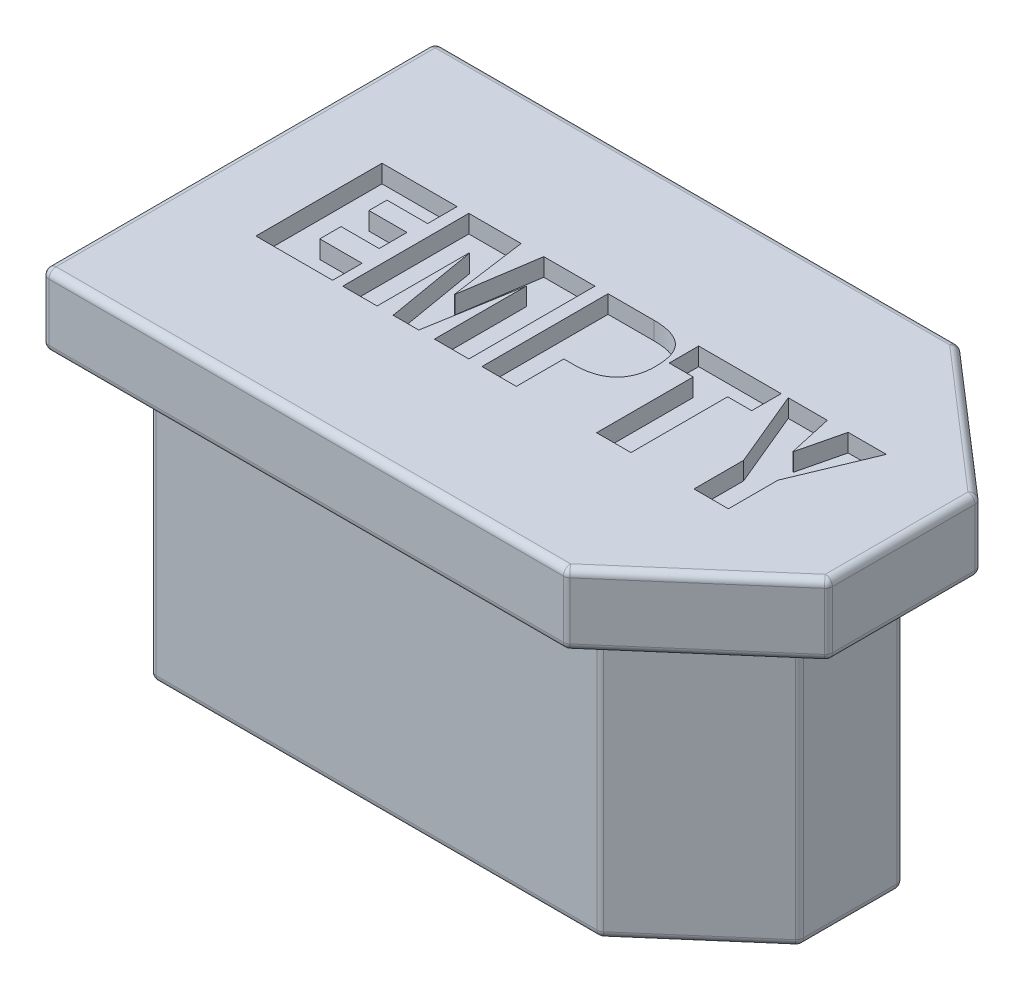
SolidWorks part; units mm, degrees
ref_plane "Front Plane" through (0, 0, 0) normal (0, 0, 1) x (1, 0, 0)
ref_plane "Top Plane" through (0, 0, 0) normal (0, 1, 0) x (1, 0, 0)
ref_plane "Right Plane" through (0, 0, 0) normal (1, 0, 0) x (0, 0, -1)
sketch "Sketch1" plane through (0, 0, 0) normal (0, 1, 0) x (1, 0, 0)
  line L0 (-7.8002, 4) -> (4.7998, 4)
  line L1 (4.7998, 4) -> (7.8002, 1.4)
  line L2 (7.8002, 1.4) -> (7.8002, -1.4)
  line L3 (7.8002, -1.4) -> (4.7998, -4)
  line L4 (4.7998, -4) -> (-7.8002, -4)
  line L5 (-7.8002, -4) -> (-7.8002, 4)
  line L6 (-7.8002, 0) -> (7.8002, 0) construction
  dimension "D1" = 8
  dimension "D2" = 12.6
  dimension "D3" = 139.09
  dimension "D4" = 2.8
extrude "Boss-Extrude1" add sketch "Sketch1" along normal mid plane 8
shell "Shell1" thickness 0.7
sketch "Sketch2" plane through (0, 4, 0) normal (0, 1, 0) x (1, 0, 0)
  line L0 (-7.8002, 4) -> (-7.8002, -4) construction
  line L1 (4.7998, 4) -> (-7.8002, 4) construction
  line L2 (7.8002, 1.4) -> (4.7998, 4) construction
  line L3 (7.8002, -1.4) -> (7.8002, 1.4) construction
  line L4 (4.7998, -4) -> (7.8002, -1.4) construction
  line L5 (-7.8002, -4) -> (4.7998, -4) construction
  line L6 (-7.8002, 4) -> (-7.8002, -4) construction
  line L7 (4.7998, 4) -> (-7.8002, 4) construction
  line L8 (7.8002, 1.4) -> (4.7998, 4) construction
  line L9 (7.8002, -1.4) -> (7.8002, 1.4) construction
  line L10 (4.7998, -4) -> (7.8002, -1.4) construction
  line L11 (-7.8002, -4) -> (4.7998, -4) construction
  line L12 (-9.3002, 5.5) -> (-9.3002, -5.5)
  line L13 (-9.3002, -5.5) -> (5.3593, -5.5)
  line L14 (5.3593, -5.5) -> (9.3002, -2.085)
  line L15 (9.3002, -2.085) -> (9.3002, 2.085)
  line L16 (9.3002, 2.085) -> (5.3593, 5.5)
  line L17 (5.3593, 5.5) -> (-9.3002, 5.5)
  dimension "D1" = 1.5
extrude "Boss-Extrude2" add sketch "Sketch2" along normal blind 2
sketch "Sketch4" plane through (0, -4, 0) normal (0, -1, 0) x (1, 0, 0)
  line L0 (-1.1002, -3.3) -> (-1.1002, -2.1)
  line L3 (4.5387, -3.3) -> (-7.1002, -3.3) construction
  line L5 (-1.1002, -2.1) -> (0.8998, -2.1)
  line L6 (0.8998, -2.1) -> (0.8998, -3.3)
  line L7 (-1.1002, -3.3) -> (0.8998, -3.3)
  dimension "D1" = 1.2
  dimension "D2" = 2
  dimension "D3" = 6
extrude "Boss-Extrude4" add sketch "Sketch4" against normal up to next
sketch "Sketch5" plane through (0, 4, 0) normal (0, -1, 0) x (1, 0, 0)
  line L0 (-0.6502, -2.1) -> (-0.6502, 1.9)
  line L1 (0.8998, -2.1) -> (-1.1002, -2.1) construction
  line L2 (-0.6502, 1.9) -> (0.4498, 1.9)
  line L3 (0.4498, 1.9) -> (0.4498, -2.1)
  line L4 (0.8998, -2.1) -> (-1.1002, -2.1) construction
  line L5 (0.4498, -2.1) -> (-0.6502, -2.1)
  line L6 (-0.1002, -2.1) -> (-0.1002, 1.9) construction
  dimension "D1" = 4
  dimension "D2" = 1.1
extrude "Cut-Extrude1" cut sketch "Sketch5" against normal blind 1
fillet "Fillet1" radius 0.2 78 edges at (4.5387, 0, -3.3) (7.1002, 0, -1.0803) (7.1002, 0, 1.0803) (4.5387, 0, 3.3) (-7.1002, 0, -3.3) (-1.1002, 0, -3.3) (-1.1002, 0, -2.1) (0.8998, 0, -2.1) (0.8998, 0, -3.3) (-7.1002, 0, 3.3) (0.8998, 4, -2.7) (0.8998, -4, -2.7) (2.7192, -4, -3.3) (-1.1002, 4, -2.7) (-1.1002, -4, -2.7) (-0.1002, 4, 1.9) (5.8195, -4, -2.1902) (-4.1002, -4, -3.3) (-0.1002, -4, -2.1) (-0.1002, 5, 1.9) (0.4498, 4.5, 1.9) (-0.6502, 4.5, 1.9) (0.4498, 5, -0.1) (-0.6502, 5, -0.1) (5.8195, 4, -2.1902) (2.7192, 4, -3.3) (-0.1002, 5, -2.1) (-4.1002, 4, -3.3) (7.1002, -4, 0) (7.1002, 4, 0) (-1.2808, -4, 3.3) (-1.2808, 4, 3.3) (5.8195, -4, 2.1902) (5.8195, 4, 2.1902) (-7.1002, -4, 0) (-7.1002, 4, 0) (-1.9705, 4, -5.5) (-9.3002, 4, 0) (-1.9705, 4, 5.5) (7.3297, 4, 3.7925) (9.3002, 4, 0) (7.3297, 4, -3.7925) (-1.9705, 6, -5.5) (-9.3002, 6, 0) (-1.9705, 6, 5.5) (7.3297, 6, 3.7925) (9.3002, 6, 0) (7.3297, 6, -3.7925) (5.3593, 5, -5.5) (9.3002, 5, -2.085) (9.3002, 5, 2.085) (5.3593, 5, 5.5) (-9.3002, 5, 5.5) (-9.3002, 5, -5.5) (-7.8002, -4, 0) (6.3, -4, 2.7) (7.8002, -4, 0) (6.3, -4, -2.7) (-1.5002, -4, -4) (-7.8002, 4, 0) (-1.5002, 4, 4) (6.3, 4, 2.7) (7.8002, 4, 0) (6.3, 4, -2.7) (-1.5002, 4, -4) (-7.8002, 0, -4) (4.7998, 0, -4) (7.8002, 0, -1.4) (7.8002, 0, 1.4) (4.7998, 0, 4) (-7.8002, 0, 4) (-1.5002, -4, 4)
sketch "Sketch6" plane through (0, 6, 0) normal (0, 1, 0) x (1, 0, 0)
  line L0 (-7.0504, 1.7632) -> (-4.9509, 1.7632)
  line L1 (-4.9509, 1.7632) -> (-4.9509, 0.9388)
  line L2 (-4.9509, 0.9388) -> (-6.0886, 0.9388)
  line L3 (-6.0886, 0.9388) -> (-6.0886, 0.4351)
  line L4 (-6.0886, 0.4351) -> (-5.0253, 0.4351)
  line L5 (-5.0253, 0.4351) -> (-5.0253, -0.3435)
  line L6 (-5.0253, -0.3435) -> (-6.0886, -0.3435)
  line L7 (-6.0886, -0.3435) -> (-6.0886, -0.9388)
  line L8 (-6.0886, -0.9388) -> (-4.9065, -0.9388)
  line L9 (-4.9065, -0.9388) -> (-4.9065, -1.7632)
  line L10 (-4.9065, -1.7632) -> (-7.0504, -1.7632)
  line L11 (-7.0504, -1.7632) -> (-7.0504, 1.7632)
  line L12 (-4.6231, 1.7632) -> (-3.1619, 1.7632)
  line L13 (-3.1619, 1.7632) -> (-2.8649, -0.3893)
  line L14 (-2.8649, -0.3893) -> (-2.8549, -0.3893)
  line L15 (-2.8549, -0.3893) -> (-2.5272, 1.7632)
  line L16 (-2.5272, 1.7632) -> (-1.0968, 1.7632)
  line L17 (-1.0968, 1.7632) -> (-1.0968, -1.7632)
  line L18 (-1.0968, -1.7632) -> (-2.0585, -1.7632)
  line L19 (-2.0585, -1.7632) -> (-2.0585, 0.8086)
  line L20 (-2.0585, 0.8086) -> (-2.4964, -1.7632)
  line L21 (-2.4964, -1.7632) -> (-3.2134, -1.7632)
  line L22 (-3.2134, -1.7632) -> (-3.6514, 0.8086)
  line L23 (-3.6514, 0.8086) -> (-3.6614, 0.8086)
  line L24 (-3.6614, 0.8086) -> (-3.6614, -1.7632)
  line L25 (-3.6614, -1.7632) -> (-4.6231, -1.7632)
  line L26 (-4.6231, -1.7632) -> (-4.6231, 1.7632)
  line L27 (-0.7304, 1.7632) -> (0.5527, 1.7632)
  line L28 (0.5333, -0.4351) -> (0.2314, -0.4351)
  line L29 (0.2314, -0.4351) -> (0.2314, -1.7632)
  line L30 (0.2314, -1.7632) -> (-0.7304, -1.7632)
  line L31 (-0.7304, 1.7632) -> (-0.7304, -1.7632)
  line L32 (-7.0504, 0) -> (7.0504, 0) construction
  line L34 (0, 0) -> (0, 1.7632) construction
  line L35 (1.8028, 1.7632) -> (4.1098, 1.7632)
  line L36 (4.1098, 1.7632) -> (4.1098, 0.9388)
  line L37 (4.1098, 0.9388) -> (3.4371, 0.9388)
  line L38 (3.4371, 0.9388) -> (3.4371, -1.7632)
  line L39 (3.4371, -1.7632) -> (2.4754, -1.7632)
  line L40 (2.4754, -1.7632) -> (2.4754, 0.9388)
  line L41 (2.4754, 0.9388) -> (1.8028, 0.9388)
  line L42 (1.8028, 0.9388) -> (1.8028, 1.7632)
  line L43 (5.982, 1.7632) -> (7.0504, 1.7632)
  line L44 (7.0504, 1.7632) -> (6.1602, -0.3757)
  line L45 (6.1602, -0.3757) -> (6.1602, -1.7632)
  line L46 (6.1602, -1.7632) -> (5.1984, -1.7632)
  line L47 (5.1984, -1.7632) -> (5.1984, -0.3757)
  line L48 (5.1984, -0.3757) -> (4.3083, 1.7632)
  line L49 (4.3083, 1.7632) -> (5.4002, 1.7632)
  line L50 (5.4002, 1.7632) -> (5.6743, 0.5317)
  line L51 (5.6743, 0.5317) -> (5.6843, 0.5317)
  line L52 (5.6843, 0.5317) -> (5.982, 1.7632)
  spline S0 degree 3 poles (0.5527, 1.7632) (0.6417, 1.7623) (0.7718, 1.7568) (0.938, 1.7296) (1.0496, 1.7008) (1.153, 1.6655) (1.2472, 1.6208) (1.3329, 1.5686) (1.4099, 1.5079) (1.4779, 1.438) (1.5361, 1.3575) (1.5858, 1.2671) (1.6265, 1.1664) (1.6578, 1.0556) (1.6878, 0.8884) (1.6959, 0.7569) (1.6954, 0.6662) knots 0 0 0 0 0.146363 0.213051 0.276109 0.335425 0.392173 0.446836 0.499792 0.552681 0.606484 0.66239 0.721576 0.784288 0.851179 1 1 1 1
  spline S1 degree 3 poles (1.6954, 0.6662) (1.6943, 0.5747) (1.6872, 0.4413) (1.6495, 0.2737) (1.6119, 0.1634) (1.5629, 0.064) (1.5077, -0.0272) (1.4415, -0.1078) (1.3677, -0.1798) (1.2857, -0.242) (1.1967, -0.2956) (1.1004, -0.3398) (0.9972, -0.3753) (0.8883, -0.4026) (0.7334, -0.4268) (0.6143, -0.4364) (0.5333, -0.4351) knots 0 0 0 0 0.150663 0.21816 0.281612 0.341727 0.399798 0.456348 0.512604 0.568801 0.625051 0.68291 0.742645 0.804042 0.867177 1 1 1 1
extrude "Cut-Extrude2" cut sketch "Sketch6" against normal blind 0.5
